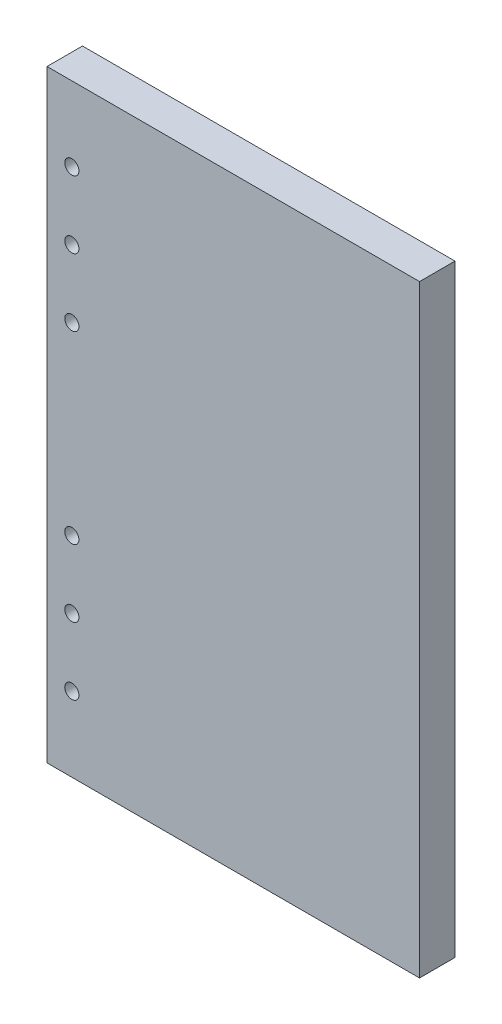
SolidWorks part; units mm, degrees
ref_plane "Спереди" through (0, 0, 0) normal (0, 0, 1) x (1, 0, 0)
ref_plane "Сверху" through (0, 0, 0) normal (0, 1, 0) x (1, 0, 0)
ref_plane "Справа" through (0, 0, 0) normal (1, 0, 0) x (0, 0, -1)
sketch "Эскиз1" plane through (0, 0, 0) normal (0, 0, 1) x (1, 0, 0)
  line L0 (0, 85) -> (105, 85) construction
  line L1 (0, 0) -> (105, 0)
  line L2 (0, 0) -> (0, 170)
  line L3 (0, 170) -> (105, 170)
  line L4 (105, 0) -> (105, 170)
  line L5 (7, 85) -> (7, 111) construction
  line L6 (7, 149) -> (7, 130) construction
  line L7 (7, 130) -> (7, 111) construction
  line L8 (7, 40) -> (7, 59) construction
  line L9 (7, 21) -> (7, 40) construction
  circle A0 centre (7, 111) radius 2
  circle A1 centre (7, 130) radius 2
  circle A2 centre (7, 149) radius 2
  circle A3 centre (7, 21) radius 2
  circle A4 centre (7, 40) radius 2
  circle A5 centre (7, 59) radius 2
  dimension "D3" = 4
  dimension "D4" = 4
  dimension "D5" = 4
  dimension "D6" = 19
  dimension "D7" = 19
  dimension "D8" = 52
  dimension "D1" = 105
  dimension "D2" = 170
  dimension "D9" = 7
extrude "Бобышка-Вытянуть1" add sketch "Эскиз1" along normal blind 10
